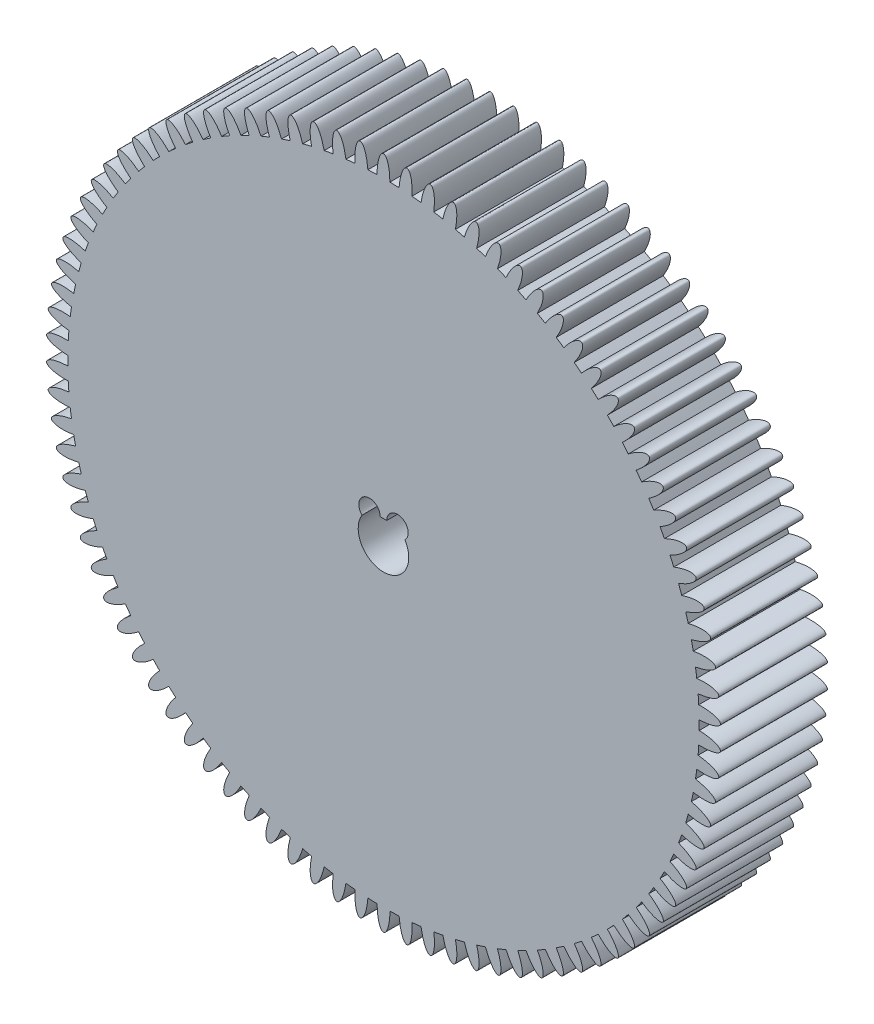
SolidWorks part; units mm, degrees
ref_plane "Front Plane" through (0, 0, 0) normal (0, 0, 1) x (1, 0, 0)
ref_plane "Top Plane" through (0, 0, 0) normal (0, 1, 0) x (1, 0, 0)
ref_plane "Right Plane" through (0, 0, 0) normal (1, 0, 0) x (0, 0, -1)
sketch "Sketch1" plane through (0, 0, 0) normal (0, 0, 1) x (1, 0, 0)
  circle A0 centre (0, 0) radius 37.465
  dimension "D1" = 74.93
extrude "Boss-Extrude1" add sketch "Sketch1" along normal mid plane 12.7
sketch "Sketch2" plane through (0, 0, 6.35) normal (0, 0, 1) x (1, 0, 0)
  line L0 (-1.6583, 2.5) -> (1.6583, 2.5)
  line L1 (55, 0) -> (-55, 0) construction
  arc A0 (-1.6583, 2.5) -> (1.6583, 2.5) centre (0, 0) ccw
  dimension "D1" = 3
  dimension "D2" = 2.5
extrude "Cut-Extrude1" cut sketch "Sketch2" against normal through all both and the other way through all
sketch "Sketch3" plane through (0, 0, 6.35) normal (0, 0, 1) x (1, 0, 0)
  circle A0 centre (-1.6583, 2.5) radius 1.27
  circle A1 centre (1.6583, 2.5) radius 1.27
  dimension "D1" = 2.54
extrude "Cut-Extrude2" cut sketch "Sketch3" against normal through all both and the other way through all
sketch "Sketch5" plane through (0, 0, 6.35) normal (0, 0, 1) x (1, 0, 0)
  line L0 (0, -55) -> (0, 55) construction
  circle A0 centre (0, 0) radius 37.465 construction
  ellipse E0 centre (0, 37.465) end of major axis (0, 40.005) minor radius 0.762
  dimension "D1" = 2.54
  dimension "D2" = 1.524
extrude "Boss-Extrude2" add sketch "Sketch5" against normal up to surface (12.7 mm away) up to face at (0, 1.71, -6.35)
ref_axis "Axis1" through (0, 0, -6.35) along (0, 0, 1)
pattern_circular "CirPattern1" count 90 over 360 about axis through (0, 0, -6.35) along (0, 0, 1) of "Boss-Extrude2"
